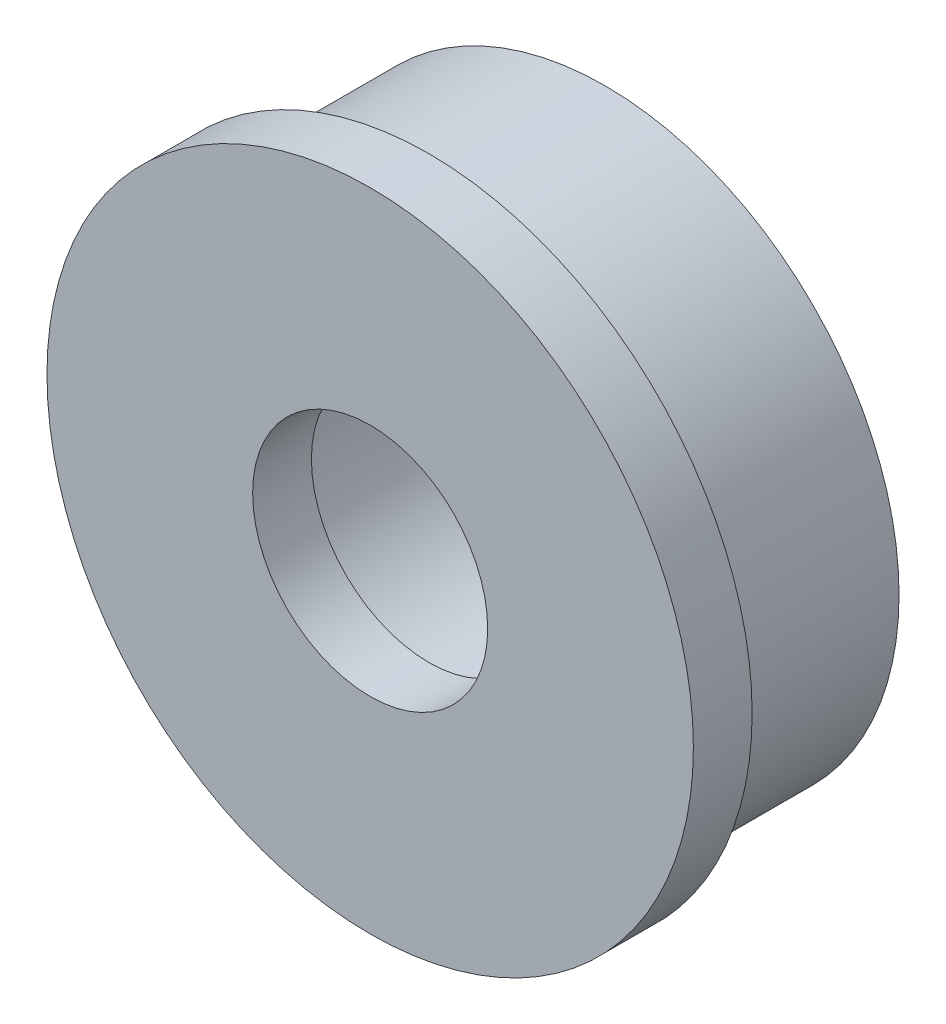
SolidWorks part; units mm, degrees
material "1.5714 (16NiCr4)"
ref_plane "前视" through (0, 0, 0) normal (0, 0, 1) x (1, 0, 0)
ref_plane "上视" through (0, 0, 0) normal (0, 1, 0) x (1, 0, 0)
ref_plane "右视" through (0, 0, 0) normal (1, 0, 0) x (0, 0, -1)
sketch "草图1" plane through (0, 0, 0) normal (0, 0, 1) x (1, 0, 0)
  circle A0 centre (0, 0) radius 5
  circle A1 centre (0, 0) radius 2.5
  dimension "D1" = 5
  dimension "D2" = 10
extrude "凸台-拉伸1" add sketch "草图1" along normal blind 3
sketch "草图2" plane through (0, 0, 3) normal (0, 0, 1) x (1, 0, 0)
  circle A0 centre (0, 0) radius 5.5
  circle A1 centre (0, 0) radius 2
  dimension "D1" = 11
extrude "凸台-拉伸2" add sketch "草图2" along normal blind 1
